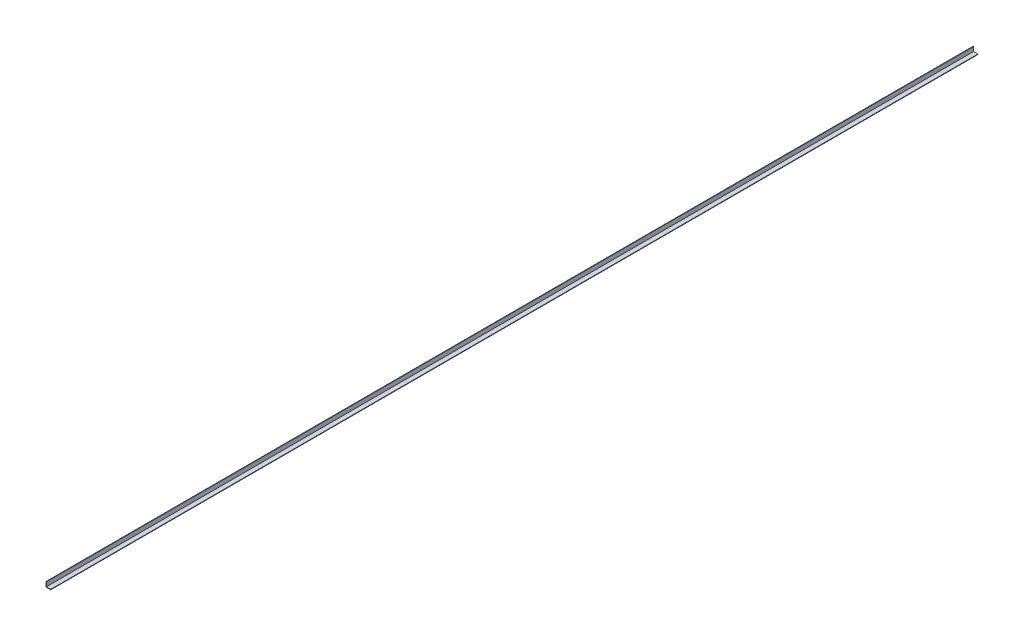
SolidWorks part; units mm, degrees
material "ASTM A36 Acero"
ref_plane "Alzado" through (0, 0, 0) normal (0, 0, 1) x (1, 0, 0)
ref_plane "Planta" through (0, 0, 0) normal (0, 1, 0) x (1, 0, 0)
ref_plane "Vista lateral" through (0, 0, 0) normal (1, 0, 0) x (0, 0, -1)
sketch "Croquis1" plane through (0, 0, 0) normal (0, 0, 1) x (1, 0, 0)
  line L0 (0, 31.75) -> (0, 0)
  line L1 (0, 0) -> (31.75, 0)
  line L2 (31.75, 0) -> (31.75, 3.18)
  line L3 (31.75, 3.18) -> (3.18, 3.18)
  line L4 (3.18, 3.18) -> (3.18, 31.75)
  line L5 (3.18, 31.75) -> (0, 31.75)
  dimension "D1" = 3.18
  dimension "D2" = 31.75
extrude "Saliente-Extruir1" add sketch "Croquis1" against normal blind 6100
